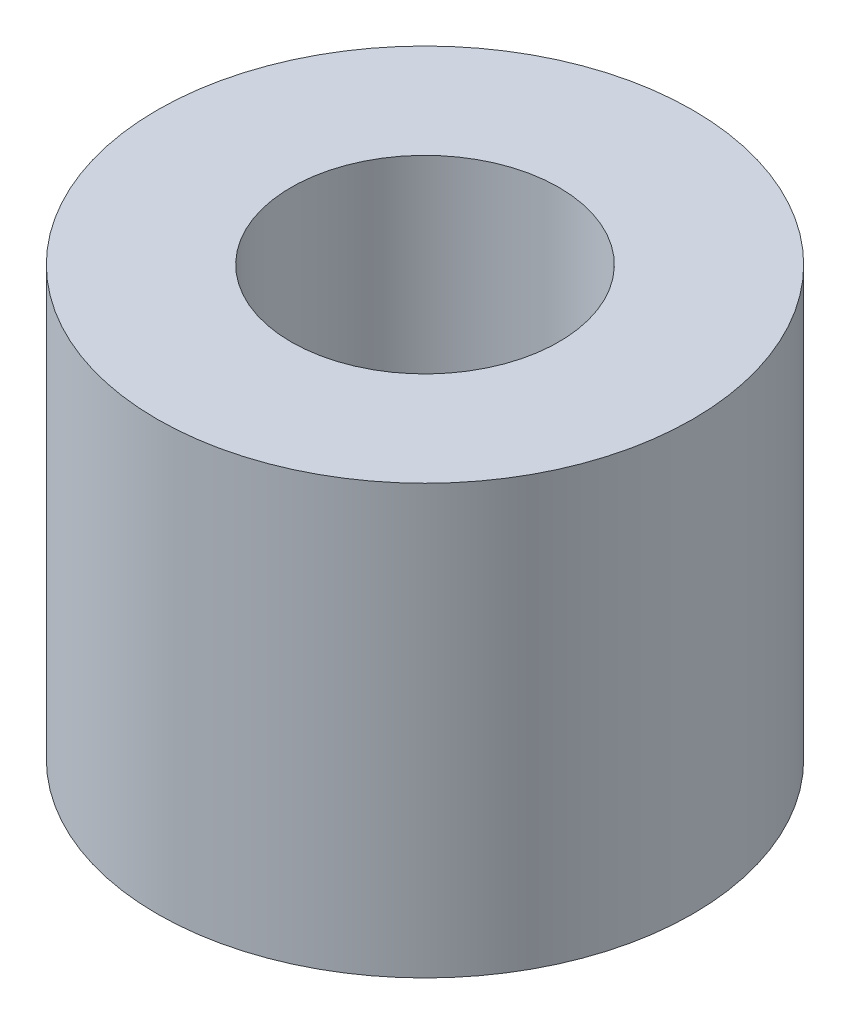
SolidWorks part; units mm, degrees
ref_plane "Front Plane" through (0, 0, 0) normal (0, 0, 1) x (1, 0, 0)
ref_plane "Top Plane" through (0, 0, 0) normal (0, 1, 0) x (1, 0, 0)
ref_plane "Right Plane" through (0, 0, 0) normal (1, 0, 0) x (0, 0, -1)
sketch "Sketch1" plane through (0, 0, 0) normal (0, 1, 0) x (1, 0, 0)
  circle A0 centre (0, 0) radius 2.5
  circle A1 centre (0, 0) radius 5
  dimension "D1" = 5
  dimension "D2" = 10
extrude "Boss-Extrude1" add sketch "Sketch1" along normal blind 8
